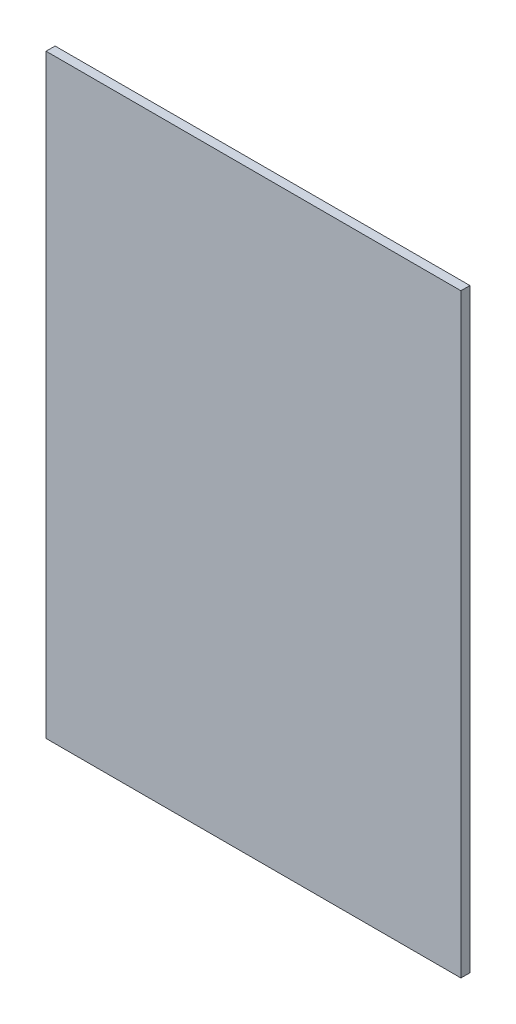
SolidWorks part; units mm, degrees
ref_plane "Alzado" through (0, 0, 0) normal (0, 0, 1) x (1, 0, 0)
ref_plane "Planta" through (0, 0, 0) normal (0, 1, 0) x (1, 0, 0)
ref_plane "Vista lateral" through (0, 0, 0) normal (1, 0, 0) x (0, 0, -1)
sketch "Croquis1" plane through (0, 0, 0) normal (0, 0, 1) x (1, 0, 0)
  line L1 (230, -330) -> (-230, -330)
  line L2 (230, -330) -> (230, 330)
  line L3 (230, 330) -> (-230, 330)
  line L4 (-230, -330) -> (-230, 330)
  line L5 (230, -330) -> (-230, 330) construction
  line L6 (230, 330) -> (-230, -330) construction
  point P0 (0, 0)
  dimension "D1" = 660
  dimension "D2" = 460
extrude "Saliente-Extruir1" add sketch "Croquis1" along normal blind 10
shell "Vaciado1" thickness 2
